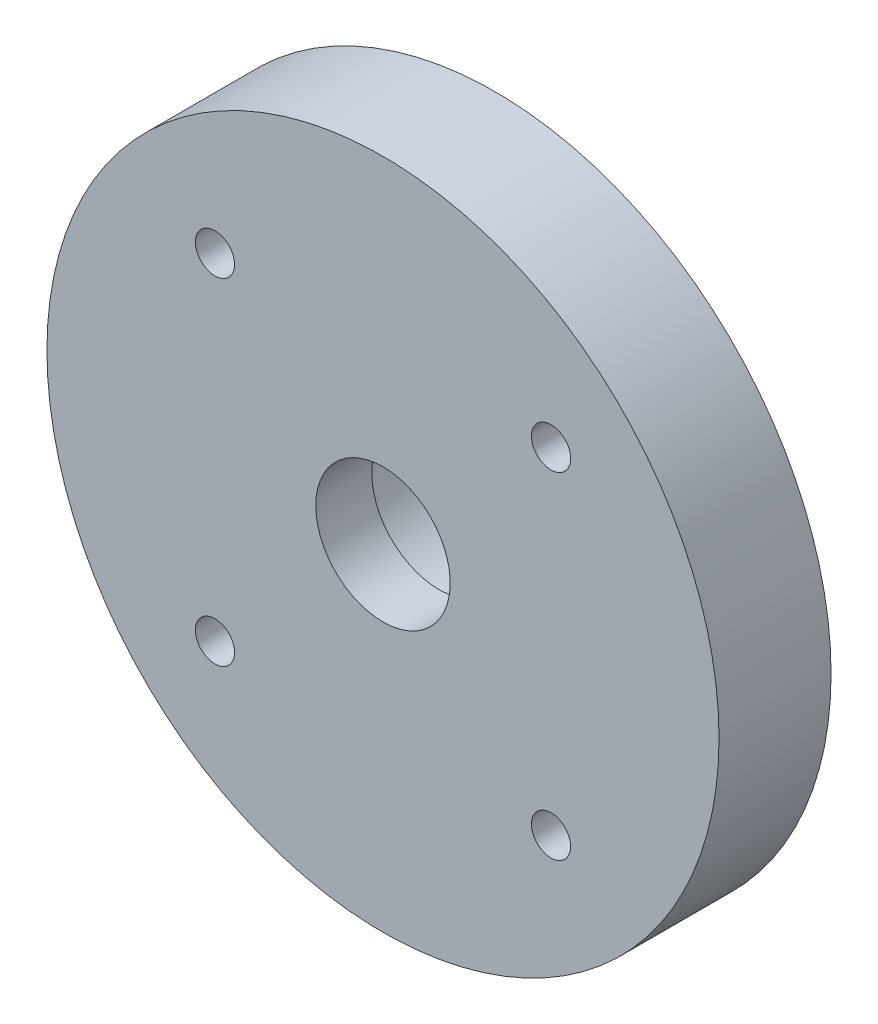
SolidWorks part; units mm, degrees
ref_plane "Front Plane" through (0, 0, 0) normal (0, 0, 1) x (1, 0, 0)
ref_plane "Top Plane" through (0, 0, 0) normal (0, 1, 0) x (1, 0, 0)
ref_plane "Right Plane" through (0, 0, 0) normal (1, 0, 0) x (0, 0, -1)
sketch "Sketch1" plane through (0, 0, 0) normal (0, 0, 1) x (1, 0, 0)
  circle A0 centre (0, 0) radius 30
  dimension "D1" = 60
extrude "Boss-Extrude1" add sketch "Sketch1" along normal blind 10
sketch "Sketch2" plane through (0, 0, 0) normal (0, 0, -1) x (-1, 0, 0)
  circle A0 centre (0, 0) radius 6
  dimension "D1" = 12
extrude "Cut-Extrude1" cut sketch "Sketch2" against normal through all
sketch "Sketch3" plane through (0, 0, 0) normal (0, 0, -1) x (-1, 0, 0)
  circle A0 centre (0, 0) radius 8
  dimension "D1" = 16
extrude "Cut-Extrude2" cut sketch "Sketch3" against normal blind 5
sketch "Sketch4" plane through (0, 0, 0) normal (0, 0, -1) x (-1, 0, 0)
  line L0 (-3.2107, 0) -> (0, 0) construction
  line L1 (0, 0) -> (0, 3.4989) construction
  circle A0 centre (-15, 15) radius 1.75
  circle A1 centre (15, 15) radius 1.75
  circle A2 centre (15, -15) radius 1.75
  circle A3 centre (-15, -15) radius 1.75
  dimension "D1" = 3.5
  dimension "D2" = 15
  dimension "D3" = 15
extrude "Cut-Extrude3" cut sketch "Sketch4" against normal through all
sketch "Sketch5" plane through (0, 0, 0) normal (0, 0, -1) x (-1, 0, 0)
  line L0 (-4.0881, 0) -> (0, 0) construction
  line L1 (-11.7091, 15) -> (-13.3546, 17.85)
  line L2 (-13.3546, 17.85) -> (-16.6454, 17.85)
  line L3 (-16.6454, 17.85) -> (-18.2909, 15)
  line L4 (-18.2909, 15) -> (-16.6454, 12.15)
  line L5 (-16.6454, 12.15) -> (-13.3546, 12.15)
  line L6 (-13.3546, 12.15) -> (-11.7091, 15)
  line L7 (0, 0) -> (0, 4.4868) construction
  line L8 (13.3546, 12.15) -> (11.7091, 15)
  line L9 (16.6454, 12.15) -> (13.3546, 12.15)
  line L10 (18.2909, 15) -> (16.6454, 12.15)
  line L11 (16.6454, 17.85) -> (18.2909, 15)
  line L12 (13.3546, 17.85) -> (16.6454, 17.85)
  line L13 (11.7091, 15) -> (13.3546, 17.85)
  line L14 (11.7091, -15) -> (13.3546, -17.85)
  line L15 (13.3546, -17.85) -> (16.6454, -17.85)
  line L16 (16.6454, -17.85) -> (18.2909, -15)
  line L17 (18.2909, -15) -> (16.6454, -12.15)
  line L18 (16.6454, -12.15) -> (13.3546, -12.15)
  line L19 (13.3546, -12.15) -> (11.7091, -15)
  line L20 (-13.3546, -12.15) -> (-11.7091, -15)
  line L21 (-16.6454, -12.15) -> (-13.3546, -12.15)
  line L22 (-18.2909, -15) -> (-16.6454, -12.15)
  line L23 (-16.6454, -17.85) -> (-18.2909, -15)
  line L24 (-13.3546, -17.85) -> (-16.6454, -17.85)
  line L25 (-11.7091, -15) -> (-13.3546, -17.85)
  circle A0 centre (-15, 15) radius 2.85 construction
  circle A1 centre (15, 15) radius 2.85 construction
  circle A2 centre (15, -15) radius 2.85 construction
  circle A3 centre (-15, -15) radius 2.85 construction
  dimension "D1" = 5.7
extrude "Cut-Extrude4" cut sketch "Sketch5" against normal blind 2
